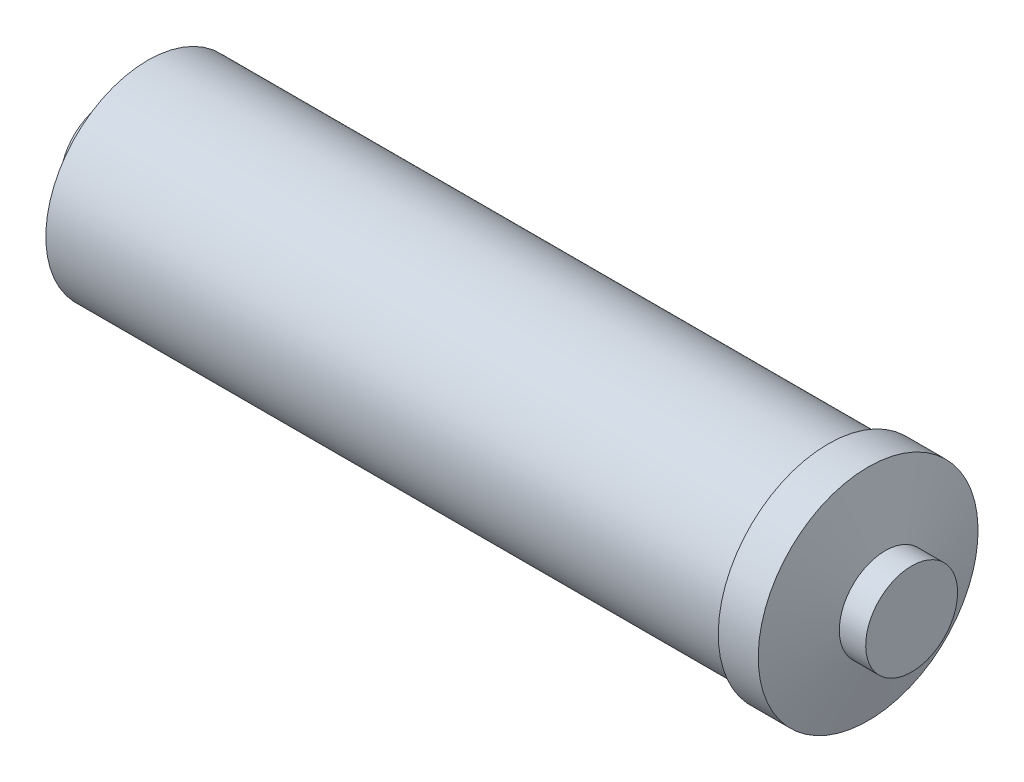
SolidWorks part; units mm, degrees
ref_plane "Front Plane" through (0, 0, 0) normal (0, 0, 1) x (1, 0, 0)
ref_plane "Top Plane" through (0, 0, 0) normal (0, 1, 0) x (1, 0, 0)
ref_plane "Right Plane" through (0, 0, 0) normal (1, 0, 0) x (0, 0, -1)
sketch "Sketch1" plane through (0, 0, 0) normal (0, 0, 1) x (1, 0, 0)
  line L0 (0, 0) -> (-255.905, 0)
  line L1 (-255.905, 0) -> (-255.905, 14.605)
  line L2 (-255.905, 14.605) -> (-247.523, 14.605)
  line L3 (-247.523, 14.605) -> (-242.7589, 32.385)
  line L4 (-242.7589, 32.385) -> (-27.2073, 32.385)
  line L5 (-27.2073, 32.385) -> (-26.5267, 34.925)
  line L6 (-26.5267, 34.925) -> (-13.8267, 34.925)
  line L7 (-13.8267, 34.925) -> (-8.382, 14.605)
  line L8 (-8.382, 14.605) -> (0, 14.605)
  line L9 (0, 14.605) -> (0, 0)
  dimension "D1" = 255.905
  dimension "D2" = 14.605
  dimension "D3" = 8.382
  dimension "D4" = 105
  dimension "D5" = 105
  dimension "D6" = 32.385
  dimension "D7" = 34.925
  dimension "D8" = 105
  dimension "D9" = 12.7
revolve "Revolve1" add sketch "Sketch1" angle 360 about L0
